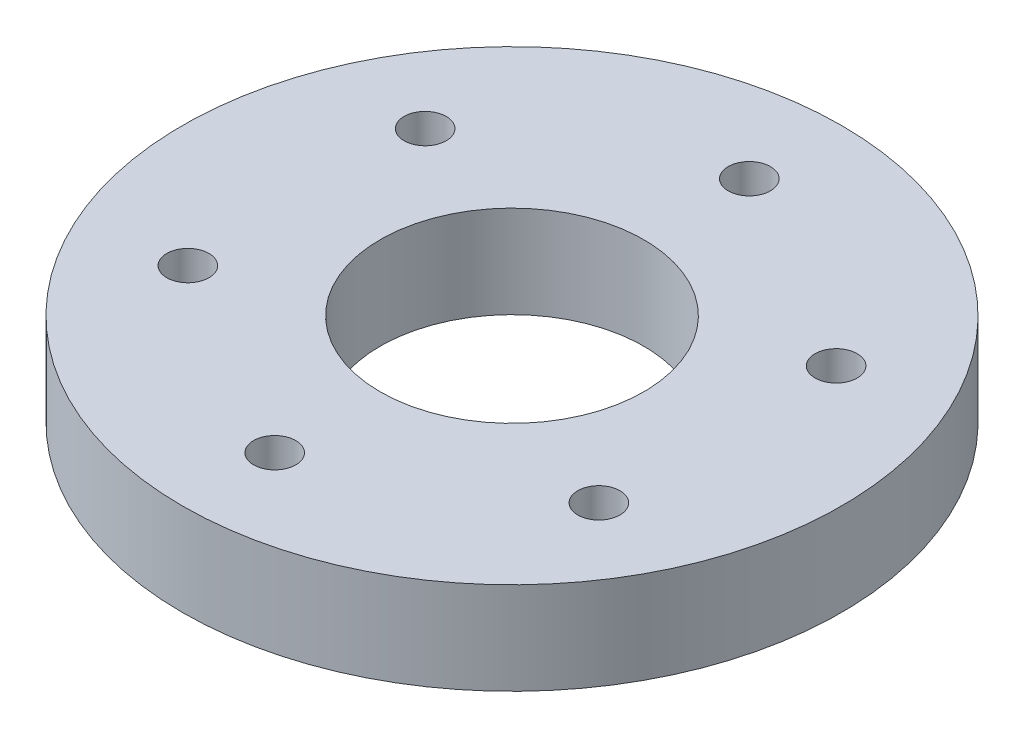
SolidWorks part; units mm, degrees
ref_plane "Front Plane" through (0, 0, 0) normal (0, 0, 1) x (1, 0, 0)
ref_plane "Top Plane" through (0, 0, 0) normal (0, 1, 0) x (1, 0, 0)
ref_plane "Right Plane" through (0, 0, 0) normal (1, 0, 0) x (0, 0, -1)
sketch "Sketch1" plane through (0, 0, 0) normal (0, 1, 0) x (1, 0, 0)
  circle A0 centre (0, 0) radius 18 construction
  circle A1 centre (0, 18) radius 3
  circle A2 centre (15.5885, 9) radius 3
  circle A3 centre (15.5885, -9) radius 3
  circle A4 centre (0, -18) radius 3
  circle A5 centre (-15.5885, -9) radius 3
  circle A6 centre (-15.5885, 9) radius 3
  point P18 (0, 0)
  dimension "D1" = 36
  dimension "D2" = 6
  dimension "D3" = 6
extrude "Boss-Extrude1" add sketch "Sketch1" along normal blind 10
sketch "Sketch2" plane through (0, 10, 0) normal (0, 1, 0) x (1, 0, 0)
  circle A0 centre (0, 0) radius 25
  dimension "D1" = 50
extrude "Boss-Extrude2" add sketch "Sketch2" along normal blind 7
sketch "Sketch3" plane through (0, 17, 0) normal (0, 1, 0) x (1, 0, 0)
  circle A0 centre (0, 0) radius 10
  dimension "D1" = 20
extrude "Cut-Extrude1" cut sketch "Sketch3" against normal through all contours A0
sketch "Sketch4" plane through (0, 17, 0) normal (0, 1, 0) x (1, 0, 0)
  circle A0 centre (0, 18) radius 1.6
  circle A1 centre (15.5885, 9) radius 1.6
  circle A2 centre (15.5885, -9) radius 1.6
  circle A3 centre (0, -18) radius 1.6
  circle A4 centre (-15.5885, -9) radius 1.6
  circle A5 centre (-15.5885, 9) radius 1.6
  point P16 (0, 0)
  dimension "D1" = 3.2
  dimension "D3" = 18
  dimension "D2" = 6
extrude "Cut-Extrude2" cut sketch "Sketch4" against normal blind 10
sketch "Sketch5" plane through (0, 0, 0) normal (0, -1, 0) x (1, 0, 0)
  line L1 (-20.0138, -23.4289) -> (26.6057, -23.4289)
  line L2 (-20.0138, -23.4289) -> (-20.0138, 23.27)
  line L3 (-20.0138, 23.27) -> (26.6057, 23.27)
  line L4 (26.6057, -23.4289) -> (26.6057, 23.27)
extrude "Cut-Extrude3" cut sketch "Sketch5" against normal up to surface (10 mm away) up to face at (0, 10, 10)
sketch "Sketch6" plane through (0, 10, 0) normal (0, -1, 0) x (-1, 0, 0)
  circle A0 centre (0, -18) radius 3
  circle A1 centre (15.5885, 9) radius 3
  circle A2 centre (-15.5885, 9) radius 3
  circle A3 centre (-15.5885, 9) radius 1.6 construction
  circle A4 centre (15.5885, 9) radius 1.6 construction
  dimension "D1" = 6
  dimension "D2" = 6
  dimension "D3" = 6
extrude "Cut-Extrude4" cut sketch "Sketch6" against normal blind 2
